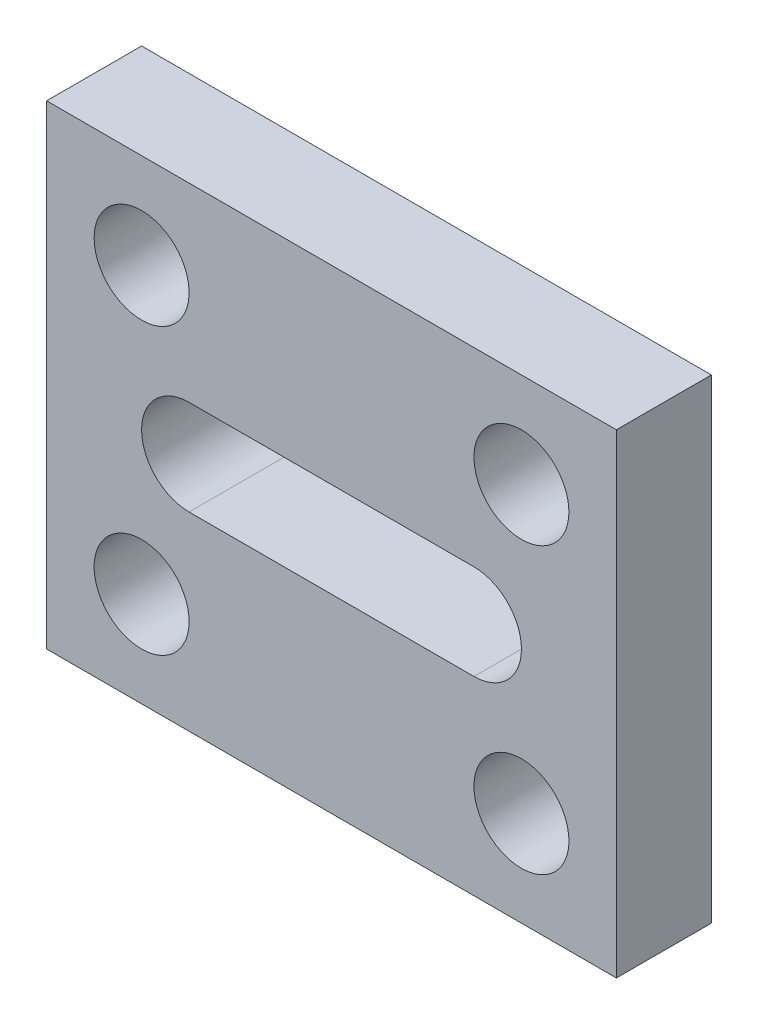
SolidWorks part; units mm, degrees
ref_plane "Front Plane" through (0, 0, 0) normal (0, 0, 1) x (1, 0, 0)
ref_plane "Top Plane" through (0, 0, 0) normal (0, 1, 0) x (1, 0, 0)
ref_plane "Right Plane" through (0, 0, 0) normal (1, 0, 0) x (0, 0, -1)
sketch "Sketch2" plane through (0, 0, 0) normal (0, 0, 1) x (1, 0, 0)
  line L3 (-60, 50) -> (60, 50)
  line L4 (-60, 50) -> (-60, -50)
  line L5 (-60, -50) -> (60, -50)
  line L6 (60, 50) -> (60, -50)
  line L7 (-30, 10) -> (30, 10)
  line L9 (-30, -10) -> (30, -10)
  arc A0 (-30, 10) -> (-30, -10) centre (-30, 0) ccw
  arc A1 (30, -10) -> (30, 10) centre (30, 0) ccw
  circle A2 centre (-40, -30) radius 10
  circle A3 centre (40, -30) radius 10
  circle A4 centre (40, 30) radius 10
  circle A5 centre (-40, 30) radius 10
  point P4 (0, 0)
  point P5 (0, 0)
  point P9 (0, 0)
  point P13 (0, 0)
extrude "Boss-Extrude1" add sketch "Sketch2" along normal blind 20
